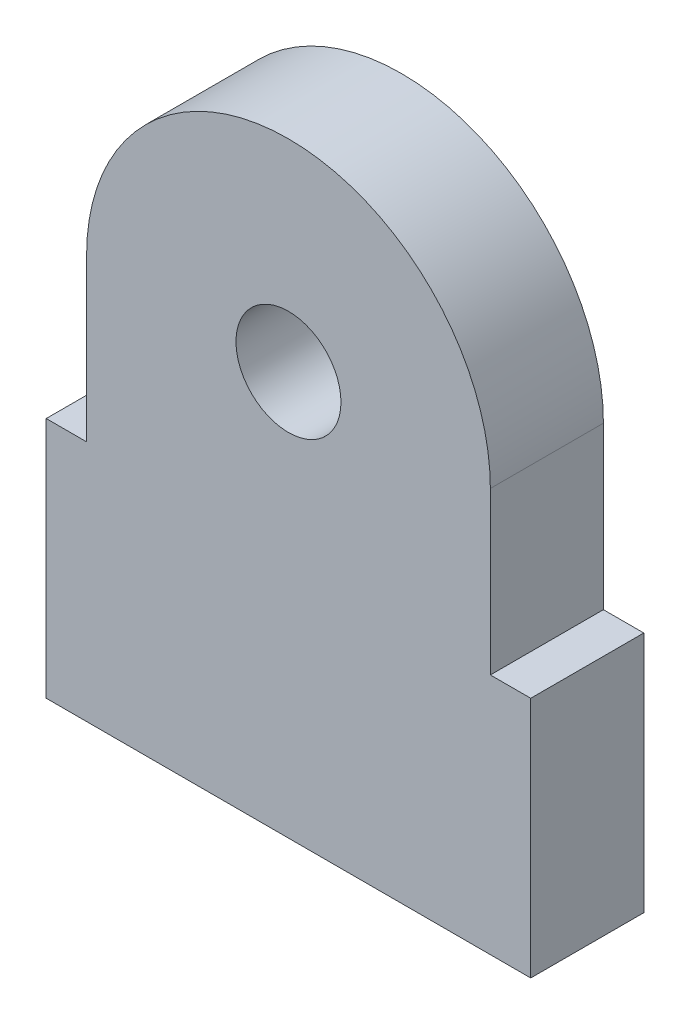
SolidWorks part; units mm, degrees
ref_plane "Ön Düzlem" through (0, 0, 0) normal (0, 0, 1) x (1, 0, 0)
ref_plane "Üst Düzlem" through (0, 0, 0) normal (0, 1, 0) x (1, 0, 0)
ref_plane "Sağ Düzlem" through (0, 0, 0) normal (1, 0, 0) x (0, 0, -1)
sketch "Çizim1" plane through (0, 0, 0) normal (0, 0, 1) x (1, 0, 0)
  line L0 (-12.5, 0) -> (-12.5, -10)
  line L1 (-15, -10) -> (-12.5, -10)
  line L2 (-15, -10) -> (-15, -25)
  line L3 (-15, -25) -> (15, -25)
  line L4 (15, -10) -> (15, -25)
  line L7 (12.5, 0) -> (12.5, -10)
  line L8 (12.5, -10) -> (15, -10)
  arc A0 (12.5, 0) -> (-12.5, 0) centre (0, 0) ccw
  point P2 (0, -17.5)
  point P10 (0, -25)
  dimension "D3" = 25
  dimension "D1" = 25
  dimension "D2" = 15
  dimension "D4" = 30
extrude "Yükseklik-Ekstrüzyon1" add sketch "Çizim1" along normal blind 7
sketch "Çizim4" plane through (0, 0, 7) normal (0, 0, 1) x (1, 0, 0)
  circle A0 centre (0, 0) radius 3.25
  dimension "D1" = 6.5
extrude "Kes-Ekstrüzyon1" cut sketch "Çizim4" against normal through all
